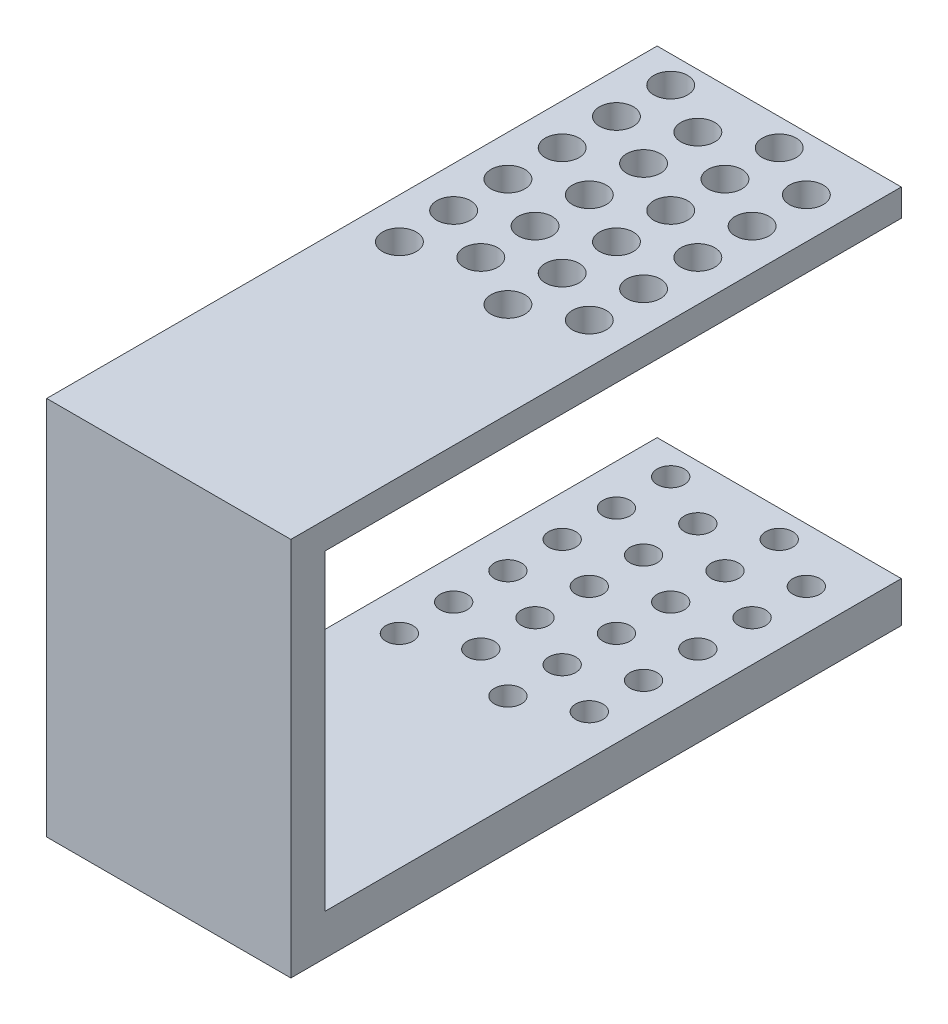
SolidWorks part; units mm, degrees
material "6061 Alloy"
ref_plane "Front Plane" through (0, 0, 0) normal (0, 0, 1) x (1, 0, 0)
ref_plane "Top Plane" through (0, 0, 0) normal (0, 1, 0) x (1, 0, 0)
ref_plane "Right Plane" through (0, 0, 0) normal (1, 0, 0) x (0, 0, -1)
sketch "Sketch2" plane through (0, 0, 0) normal (0, 1, 0) x (1, 0, 0)
  line L1 (-20, 16) -> (-2, 16)
  line L2 (-20, 16) -> (-20, -8)
  line L3 (-20, -8) -> (-2, -8)
  line L4 (-2, 16) -> (-2, -8)
  circle A0 centre (-17, -6) radius 1.25
  circle A1 centre (-17, -2) radius 1.25
  circle A2 centre (-17, 2) radius 1.25
  circle A3 centre (-17, 6) radius 1.25
  circle A4 centre (-17, 10) radius 1.25
  circle A5 centre (-17, 14) radius 1.25
  circle A6 centre (-13, -4) radius 1.25
  circle A7 centre (-13, 0) radius 1.25
  circle A8 centre (-13, 4) radius 1.25
  circle A9 centre (-13, 8) radius 1.25
  circle A10 centre (-13, 12) radius 1.25
  circle A11 centre (-9, -6) radius 1.25
  circle A12 centre (-9, -2) radius 1.25
  circle A13 centre (-9, 2) radius 1.25
  circle A14 centre (-9, 6) radius 1.25
  circle A15 centre (-9, 10) radius 1.25
  circle A16 centre (-9, 14) radius 1.25
  circle A17 centre (-5, -4) radius 1.25
  circle A18 centre (-5, 0) radius 1.25
  circle A19 centre (-5, 4) radius 1.25
  circle A20 centre (-5, 8) radius 1.25
  circle A21 centre (-5, 12) radius 1.25
  dimension "D1" = 24
  dimension "D2" = 18
extrude "Boss-Extrude2" add sketch "Sketch2" along normal blind 2
sketch "Sketch3" plane through (0, 0, 8) normal (0, 0, 1) x (1, 0, 0)
  line L1 (-20, 2) -> (-2, 2)
  line L2 (-20, 2) -> (-20, 0)
  line L3 (-20, 0) -> (-2, 0)
  line L4 (-2, 2) -> (-2, 0)
extrude "Boss-Extrude3" add sketch "Sketch3" along normal blind 21
sketch "Sketch4" plane through (0, 0, 0) normal (0, -1, 0) x (-1, 0, 0)
  line L0 (20, 16) -> (20, -29) construction
  line L1 (2, -29) -> (20, -29)
  line L2 (2, -29) -> (2, -26.5)
  line L3 (2, -26.5) -> (20, -26.5)
  line L4 (20, -29) -> (20, -26.5)
  dimension "D1" = 2.5
extrude "Boss-Extrude4" add sketch "Sketch4" along normal blind 26
sketch "Sketch5" plane through (0, 0, 26.5) normal (0, 0, -1) x (-1, 0, 0)
  line L0 (20, -26) -> (20, 0) construction
  line L1 (2, -26) -> (20, -26)
  line L2 (2, -26) -> (2, -23)
  line L3 (2, -23) -> (20, -23)
  line L4 (20, -26) -> (20, -23)
  dimension "D1" = 3
extrude "Boss-Extrude5" add sketch "Sketch5" along normal blind 42.5
sketch "Sketch15" plane through (0, -23, 0) normal (0, 1, 0) x (1, 0, 0)
  circle A0 centre (-17, -6) radius 1
  circle A1 centre (-17, -2) radius 1
  circle A2 centre (-17, 2) radius 1
  circle A3 centre (-17, 6) radius 1
  circle A4 centre (-17, 10) radius 1
  circle A5 centre (-17, 14) radius 1
  circle A6 centre (-13, -4) radius 1
  circle A7 centre (-13, 0) radius 1
  circle A8 centre (-13, 4) radius 1
  circle A9 centre (-13, 8) radius 1
  circle A10 centre (-13, 12) radius 1
  circle A11 centre (-9, -6) radius 1
  circle A12 centre (-9, -2) radius 1
  circle A13 centre (-9, 2) radius 1
  circle A14 centre (-9, 6) radius 1
  circle A15 centre (-9, 10) radius 1
  circle A16 centre (-9, 14) radius 1
  circle A17 centre (-5, -4) radius 1
  circle A18 centre (-5, 0) radius 1
  circle A19 centre (-5, 4) radius 1
  circle A20 centre (-5, 8) radius 1
  circle A21 centre (-5, 12) radius 1
extrude "Cut-Extrude3" cut sketch "Sketch15" against normal blind 2
